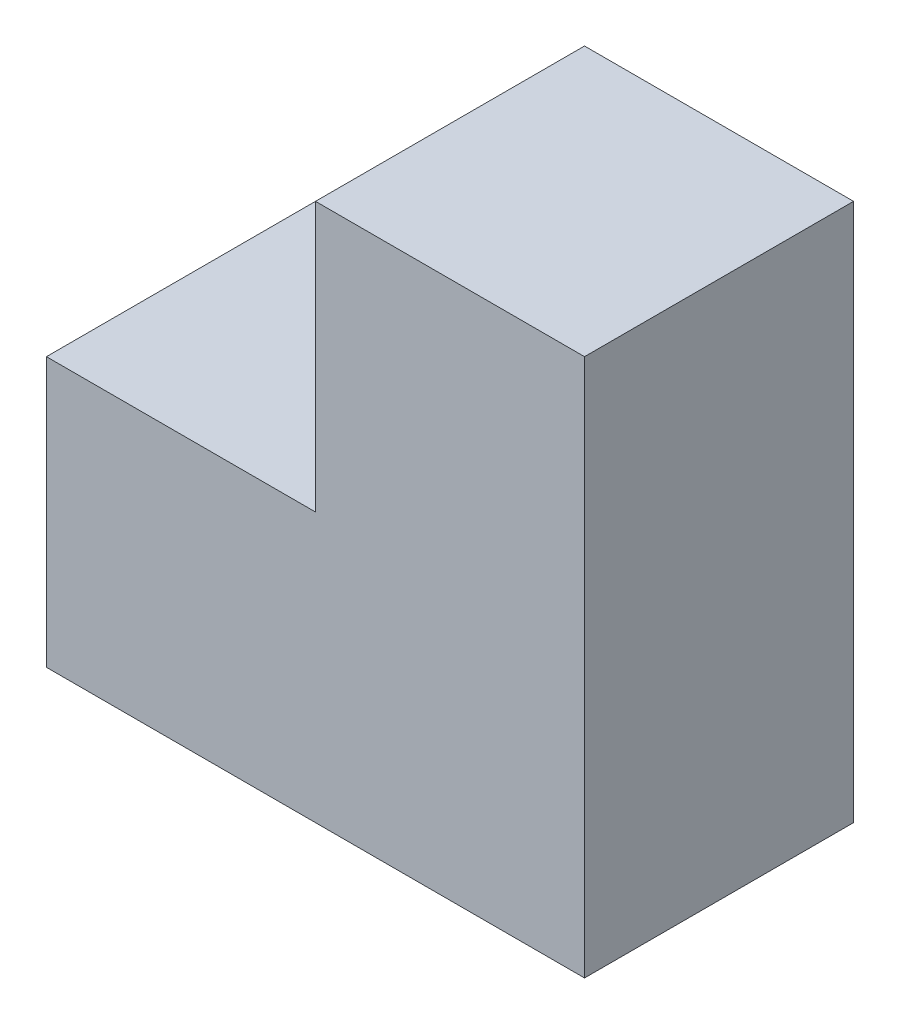
SolidWorks part; units mm, degrees
ref_plane "Front Plane" through (0, 0, 0) normal (0, 0, 1) x (1, 0, 0)
ref_plane "Top Plane" through (0, 0, 0) normal (0, 1, 0) x (1, 0, 0)
ref_plane "Right Plane" through (0, 0, 0) normal (1, 0, 0) x (0, 0, -1)
sketch "Sketch1" plane through (0, 0, 0) normal (0, 0, 1) x (1, 0, 0)
  line L0 (0, 0) -> (38.1, 0)
  line L1 (38.1, 0) -> (38.1, 38.1)
  line L2 (38.1, 38.1) -> (19.05, 38.1)
  line L3 (19.05, 38.1) -> (19.05, 19.05)
  line L4 (19.05, 19.05) -> (0, 19.05)
  line L5 (0, 19.05) -> (0, 0)
  dimension "D1" = 38.1
  dimension "D2" = 38.1
  dimension "D3" = 19.05
  dimension "D4" = 19.05
extrude "Boss-Extrude1" add sketch "Sketch1" along normal blind 19.05 contours L5 L0 L1 L2 L3 L4
